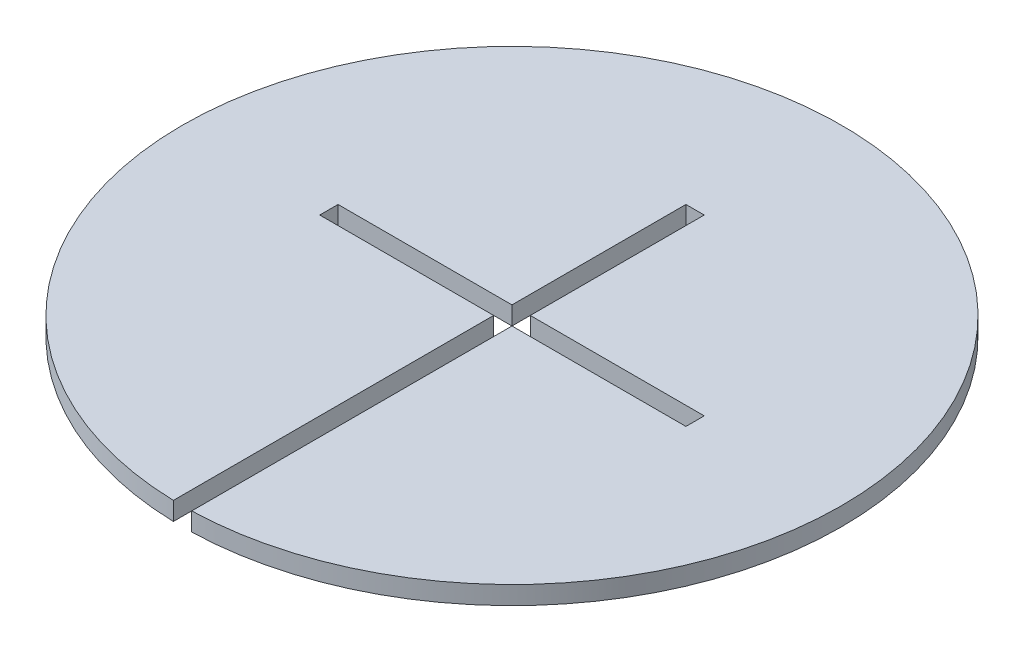
SolidWorks part; units mm, degrees
ref_plane "Front Plane" through (0, 0, 0) normal (0, 0, 1) x (1, 0, 0)
ref_plane "Top Plane" through (0, 0, 0) normal (0, 1, 0) x (1, 0, 0)
ref_plane "Right Plane" through (0, 0, 0) normal (1, 0, 0) x (0, 0, -1)
sketch "Sketch1" plane through (0, 0, 0) normal (0, 1, 0) x (1, 0, 0)
  circle A0 centre (0, 0) radius 114.3
  dimension "D1" = 228.6
extrude "Boss-Extrude1" add sketch "Sketch1" along normal blind 6.35
sketch "Sketch2" plane through (0, 6.35, 0) normal (0, 1, 0) x (1, 0, 0)
  line L0 (0, 0) -> (0, -114.3) construction
  line L2 (-3.175, -114.3) -> (3.175, -114.3)
  line L3 (-3.175, -114.3) -> (-3.175, 0)
  line L4 (-3.175, 0) -> (3.175, 0)
  line L5 (3.175, -114.3) -> (3.175, 0)
  line L6 (-3.175, -114.3) -> (3.175, 0) construction
  line L7 (-3.175, 0) -> (3.175, -114.3) construction
  circle A0 centre (0, 0) radius 114.3 construction
  point P5 (0, -57.15)
  dimension "D1" = 6.35
extrude "Cut-Extrude1" cut sketch "Sketch2" against normal blind 6.35
sketch "Sketch3" plane through (0, 6.35, 0) normal (0, 1, 0) x (1, 0, 0)
  line L1 (-63.5, 3.175) -> (63.5, 3.175)
  line L2 (-63.5, 3.175) -> (-63.5, -3.175)
  line L3 (-63.5, -3.175) -> (63.5, -3.175)
  line L4 (63.5, 3.175) -> (63.5, -3.175)
  line L5 (-63.5, 3.175) -> (63.5, -3.175) construction
  line L6 (-63.5, -3.175) -> (63.5, 3.175) construction
  point P0 (0, 0)
  dimension "D1" = 127
  dimension "D2" = 6.35
extrude "Cut-Extrude2" cut sketch "Sketch3" against normal through all
sketch "Sketch4" plane through (0, 6.35, 0) normal (0, 1, 0) x (1, 0, 0)
  line L0 (0, 0) -> (0, 50000) construction
  line L1 (63.5, -3.175) -> (63.5, 3.175) construction
  line L2 (-3.175, 63.5) -> (3.175, 63.5)
  line L3 (-3.175, 63.5) -> (-3.175, 0)
  line L4 (-3.175, 0) -> (3.175, 0)
  line L5 (3.175, 63.5) -> (3.175, 0)
  line L6 (-3.175, 63.5) -> (3.175, 0) construction
  line L7 (-3.175, 0) -> (3.175, 63.5) construction
  point P3 (0, 31.75)
  point P8 (0, 0)
  point P9 (5.464, 0)
  dimension "D1" = 63.5
extrude "Cut-Extrude3" cut sketch "Sketch4" against normal through all
